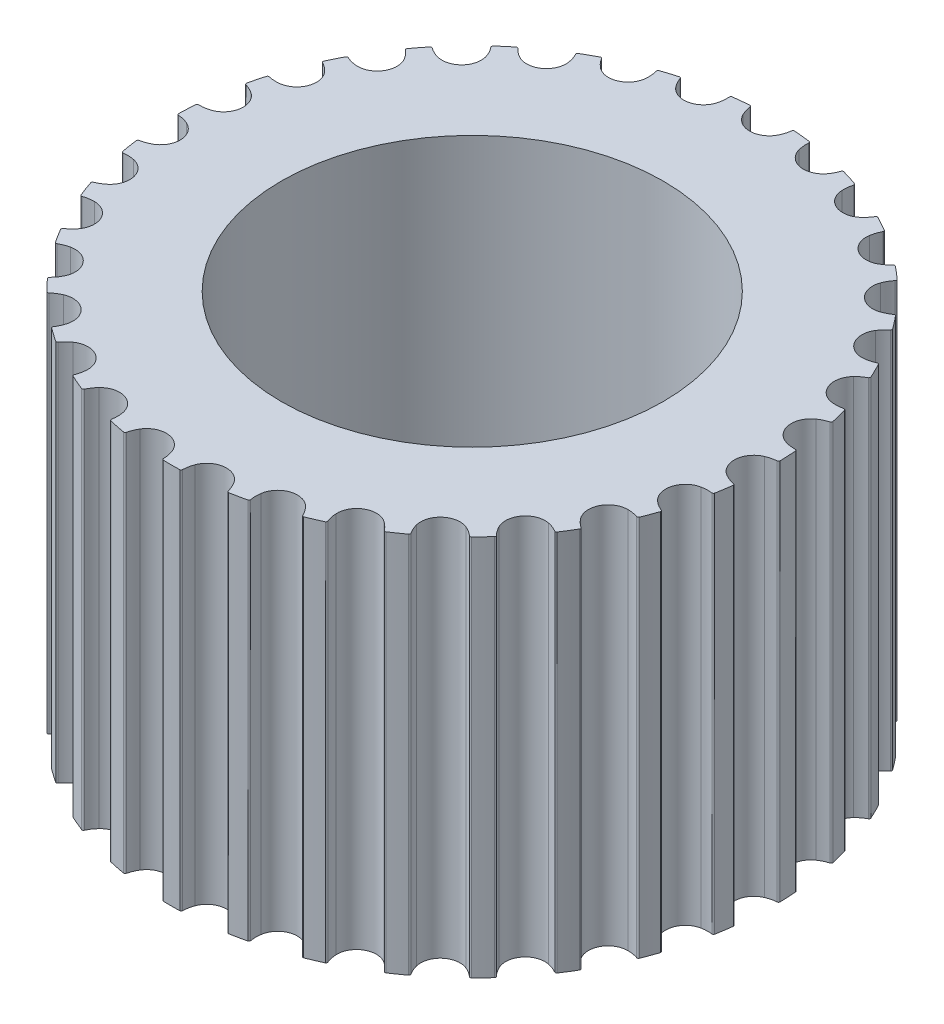
SolidWorks part; units mm, degrees
ref_plane "Front Plane" through (0, 0, 0) normal (0, 0, 1) x (1, 0, 0)
ref_plane "Top Plane" through (0, 0, 0) normal (0, 1, 0) x (1, 0, 0)
ref_plane "Right Plane" through (0, 0, 0) normal (1, 0, 0) x (0, 0, -1)
other "Default"
sketch "Sketch1" plane through (0, 0, 0) normal (0, 1, 0) x (1, 0, 0)
  circle A0 centre (0, 0) radius 6.35
  circle A1 centre (0, 0) radius 10
  dimension "ID" = 12.7
  dimension "OD" = 20
extrude "Boss-Extrude1" add sketch "Sketch1" along normal mid plane 12.7
sketch "Sketch2" plane through (0, 6.35, 0) normal (0, 1, 0) x (1, 0, 0)
  line L0 (0, 27.6626) -> (0, 29.4664) construction
  line L1 (-0.4, 10.0726) -> (0.4, 10.0726) construction
  line L2 (-0.8476, 10.0726) -> (1.0421, 10.0726) construction
  arc A0 (-0.4989, 9.6344) -> (0.4989, 9.6344) centre (0, 9.8776) ccw construction
  arc A1 (-0.4989, 9.6344) -> (-0.5915, 9.9421) centre (0.4, 10.0726) cw construction
  arc A2 (-0.5915, 9.9421) -> (-0.7402, 10.0726) centre (-0.7402, 9.9226) ccw construction
  arc A3 (0.4989, 9.6344) -> (0.5915, 9.9421) centre (-0.4, 10.0726) ccw construction
  arc A4 (0.5915, 9.9421) -> (0.7402, 10.0726) centre (0.7402, 9.9226) cw construction
  arc A6 (0.6906, 9.9291) -> (0.7402, 9.9726) centre (0.7402, 9.9226) cw
  arc A7 (0.5888, 9.5905) -> (0.6906, 9.9291) centre (-0.4, 10.0726) ccw
  arc A8 (-0.5888, 9.5905) -> (0.5888, 9.5905) centre (0, 9.8776) ccw
  arc A9 (-0.5888, 9.5905) -> (-0.6906, 9.9291) centre (0.4, 10.0726) cw
  arc A10 (-0.6906, 9.9291) -> (-0.7402, 9.9726) centre (-0.7402, 9.9226) ccw
  circle A11 centre (0, 0) radius 10 construction
  arc A12 (-0.7402, 9.9726) -> (0.7402, 9.9726) centre (0, 0) cw
  point P13 (0, 10.0726)
  point P15 (0, 9.3226)
  dimension "D1" = 0.555
  dimension "D2" = 1
  dimension "D3" = 0.15
  dimension "D4" = 0.4
  dimension "D5" = 0.75
  dimension "D6" = 0.1
extrude "Cut-Extrude1" cut sketch "Sketch2" against normal through all
pattern_circular "CirPattern1" count 31 over 360 about axis through (0, 0, 0) along (0, 1, 0) of "Cut-Extrude1"
